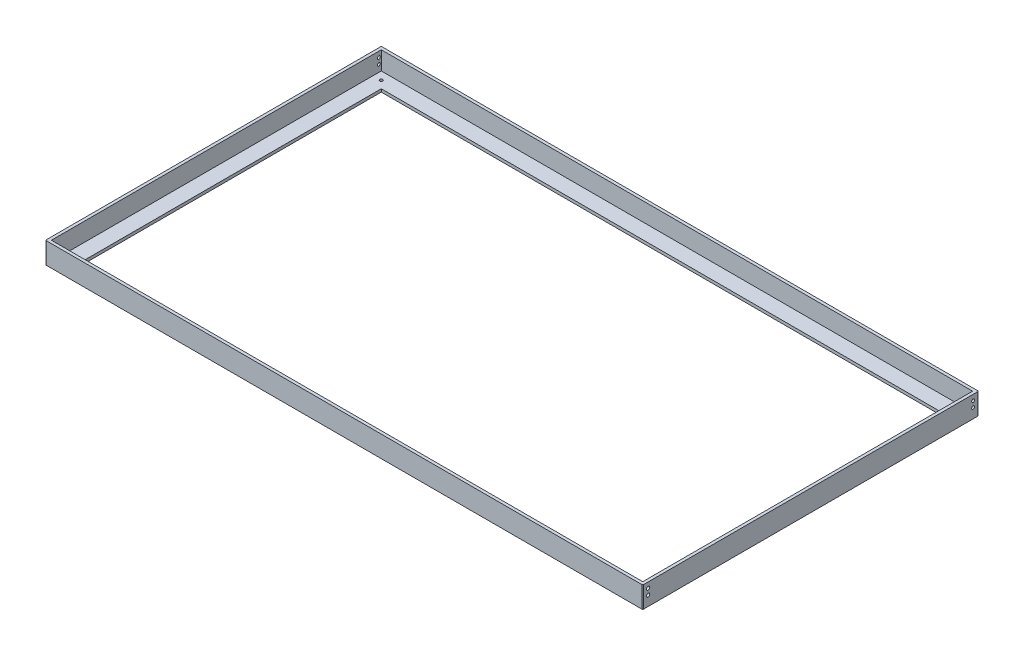
SolidWorks part; units mm, degrees
ref_plane "Front Plane" through (0, 0, 0) normal (0, 0, 1) x (1, 0, 0)
ref_plane "Top Plane" through (0, 0, 0) normal (0, 1, 0) x (1, 0, 0)
ref_plane "Right Plane" through (0, 0, 0) normal (1, 0, 0) x (0, 0, -1)
sketch "Sketch2" plane through (0, 0, 0) normal (0, 1, 0) x (1, 0, 0)
  line L1 (0, 0) -> (1626.4, 0)
  line L2 (0, 0) -> (0, 914.4)
  line L3 (0, 914.4) -> (1626.4, 914.4)
  line L4 (1626.4, 0) -> (1626.4, 914.4)
  dimension "D1" = 1626.4
  dimension "D2" = 914.4
extrude "Boss-Extrude1" add sketch "Sketch2" along normal blind 100
shell "Shell1" thickness 10
sketch "Sketch3" plane through (0, 10, 0) normal (0, 1, 0) x (1, 0, 0)
  line L0 (10, 904.4) -> (10, 10) construction
  line L1 (50, 864.4) -> (1576.4, 864.4)
  line L2 (50, 864.4) -> (50, 50)
  line L3 (50, 50) -> (1576.4, 50)
  line L4 (1576.4, 864.4) -> (1576.4, 50)
  line L5 (1616.4, 904.4) -> (10, 904.4) construction
  line L6 (1616.4, 10) -> (1616.4, 904.4) construction
  line L7 (10, 10) -> (1616.4, 10) construction
  dimension "D1" = 40
  dimension "D2" = 40
  dimension "D3" = 40
  dimension "D4" = 40
extrude "Cut-Extrude1" cut sketch "Sketch3" against normal through all
sketch "Sketch8" plane through (1626.4, 0, 0) normal (1, 0, 0) x (0, 0, -1)
  line L0 (914.4, 100) -> (914.4, 0) construction
  line L1 (0, 100) -> (914.4, 100)
  line L2 (0, 100) -> (0, 58)
  line L3 (0, 58) -> (914.4, 58)
  line L4 (914.4, 100) -> (914.4, 58)
  dimension "D1" = 42
extrude "Cut-Extrude5" cut sketch "Sketch8" against normal through all
sketch "Sketch9" plane through (1626.4, 0, 0) normal (1, 0, 0) x (0, 0, -1)
  line L2 (914.4, 58) -> (899.7, 58) construction
  line L3 (0, 58) -> (914.4, 58) construction
  line L4 (899.7, 58) -> (899.7, 43) construction
  line L5 (899.7, 43) -> (899.7, 26.7) construction
  circle A1 centre (899.7, 43) radius 4
  circle A2 centre (899.7, 26.7) radius 4
  dimension "D1" = 15
  dimension "D3" = 8
  dimension "D5" = 8
  dimension "D2" = 14.7
  dimension "D4" = 16.3
extrude "Cut-Extrude8" cut sketch "Sketch9" against normal through all
sketch "Sketch10" plane through (0, 10, 0) normal (0, 1, 0) x (1, 0, 0)
  line L0 (50, 864.4) -> (30, 864.4) construction
  line L1 (30, 864.4) -> (30, 884.4) construction
  line L2 (50, 50) -> (30, 50) construction
  line L3 (30, 50) -> (30, 30) construction
  line L4 (1576.4, 50) -> (1576.4, 30) construction
  line L5 (1576.4, 30) -> (1596.4, 30) construction
  line L6 (1576.4, 864.4) -> (1576.4, 884.4) construction
  line L7 (1576.4, 884.4) -> (1596.4, 884.4) construction
  circle A0 centre (30, 884.4) radius 4
  circle A1 centre (30, 30) radius 4
  circle A2 centre (1596.4, 30) radius 4
  circle A3 centre (1596.4, 884.4) radius 4
  dimension "D3" = 20
  dimension "D4" = 20
  dimension "D1" = 20
  dimension "D2" = 20
extrude "Cut-Extrude9" cut sketch "Sketch10" against normal through all
sketch "Sketch11" plane through (0, 58, 0) normal (0, 1, 0) x (1, 0, 0)
  line L0 (10, 904.4) -> (10, 906.4) construction
  line L1 (10, 906.4) -> (8, 906.4) construction
  line L2 (1616.4, 904.4) -> (1616.4, 10) construction
  line L3 (8, 906.4) -> (1618.4, 906.4)
  line L4 (8, 906.4) -> (8, 8)
  line L5 (8, 8) -> (1618.4, 8)
  line L6 (1618.4, 906.4) -> (1618.4, 8)
  line L7 (10, 10) -> (1616.4, 10) construction
  dimension "D1" = 2
  dimension "D2" = 2
  dimension "D3" = 2
  dimension "D4" = 2
extrude "Cut-Extrude10" cut sketch "Sketch11" against normal blind 50
fillet "Fillet1" radius 2.4 4 edges at (0, 29, 0) (1626.4, 29, 0) (1626.4, 29, -914.4) (0, 29, -914.4)
sketch "Sketch12" plane through (1626.4, 0, 0) normal (1, 0, 0) x (0, 0, -1)
  line L0 (0, 58) -> (14.7, 58) construction
  line L1 (2.4, 58) -> (912, 58) construction
  line L2 (14.7, 58) -> (14.7, 43) construction
  dimension "D1" = 14.7
  dimension "D2" = 15
sketch "Sketch13" plane through (1626.4, 0, 0) normal (1, 0, 0) x (0, 0, -1)
  circle A0 centre (14.7, 43) radius 4.5
  circle A1 centre (14.627, 26.7) radius 4.5
  point P5 (0, 0)
  dimension "D1" = 9
  dimension "D2" = 9
  dimension "D3" = 16.3
extrude "Cut-Extrude11" cut sketch "Sketch13" against normal through all
